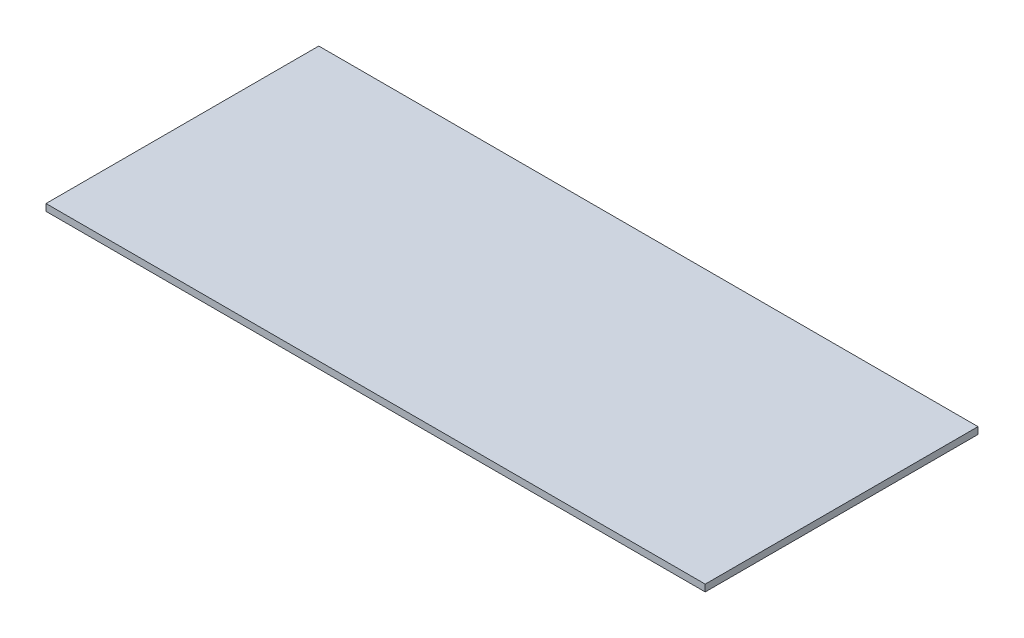
SolidWorks part; units mm, degrees
ref_plane "Front Plane" through (0, 0, 0) normal (0, 0, 1) x (1, 0, 0)
ref_plane "Top Plane" through (0, 0, 0) normal (0, 1, 0) x (1, 0, 0)
ref_plane "Right Plane" through (0, 0, 0) normal (1, 0, 0) x (0, 0, -1)
sketch "Sketch1" plane through (0, 0, 0) normal (0, 1, 0) x (1, 0, 0)
  line L1 (0, 0) -> (290, 0)
  line L2 (0, 0) -> (0, 120)
  line L3 (0, 120) -> (290, 120)
  line L4 (290, 0) -> (290, 120)
  dimension "D1" = 120
  dimension "D2" = 290
extrude "Boss-Extrude1" add sketch "Sketch1" along normal blind 3
